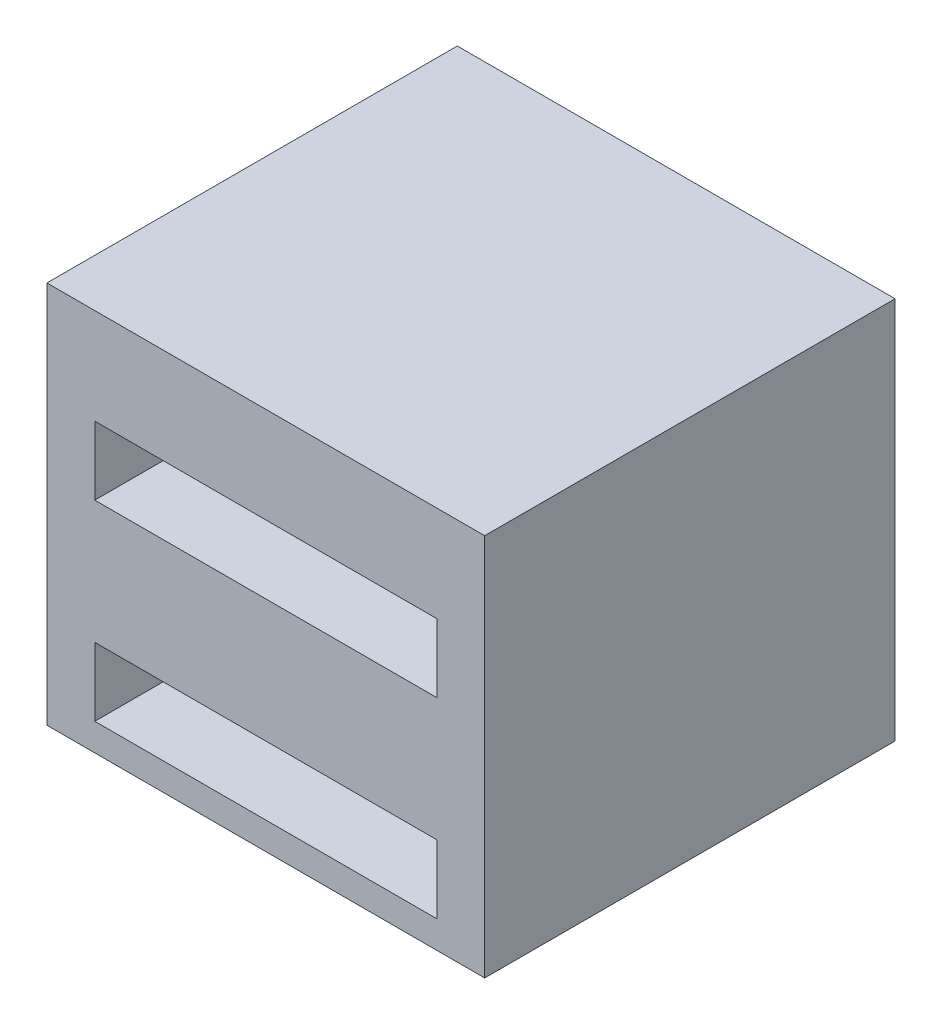
SolidWorks part; units mm, degrees
ref_plane "Front Plane" through (0, 0, 0) normal (0, 0, 1) x (1, 0, 0)
ref_plane "Top Plane" through (0, 0, 0) normal (0, 1, 0) x (1, 0, 0)
ref_plane "Right Plane" through (0, 0, 0) normal (1, 0, 0) x (0, 0, -1)
other "Configuration Table"
sketch "Sketch1" plane through (0, 0, 0) normal (0, 0, 1) x (1, 0, 0)
  line L1 (30, 1120) -> (670, 1120)
  line L2 (30, 1120) -> (30, 1680)
  line L3 (30, 1680) -> (670, 1680)
  line L4 (670, 1120) -> (670, 1680)
extrude "OVEN_OMAKE_firin_SATIN_ALINAN_64x60x56_1" add sketch "Sketch1" against normal blind 600 separate body
sketch "Sketch2" plane through (0, 0, 0) normal (0, 0, 1) x (1, 0, 0)
  line L1 (100, 1160) -> (600, 1160)
  line L2 (100, 1160) -> (100, 1260)
  line L3 (100, 1260) -> (600, 1260)
  line L4 (600, 1160) -> (600, 1260)
extrude "OVEN_OMAKE_firin_SATIN_ALINAN_64x60x56_2" cut sketch "Sketch2" against normal blind 421 from offset 1
sketch "Sketch3" plane through (0, 0, 0) normal (0, 0, 1) x (1, 0, 0)
  line L1 (100, 1440) -> (600, 1440)
  line L2 (100, 1440) -> (100, 1540)
  line L3 (100, 1540) -> (600, 1540)
  line L4 (600, 1440) -> (600, 1540)
extrude "OVEN_OMAKE_firin_SATIN_ALINAN_64x60x56_3" cut sketch "Sketch3" against normal blind 421 from offset 1
